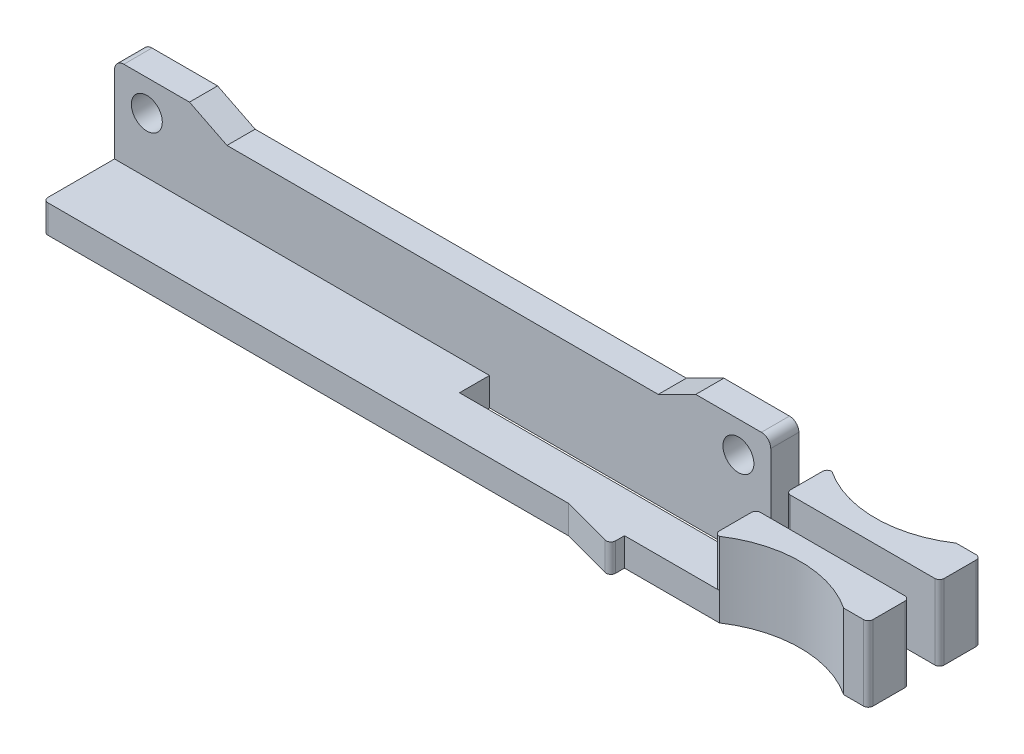
SolidWorks part; units mm, degrees
ref_plane "正面" through (0, 0, 0) normal (0, 0, 1) x (1, 0, 0)
ref_plane "平面" through (0, 0, 0) normal (0, 1, 0) x (1, 0, 0)
ref_plane "右側面" through (0, 0, 0) normal (1, 0, 0) x (0, 0, -1)
sketch "ｽｹｯﾁ2" plane through (0, 0, 0) normal (0, 1, 0) x (1, 0, 0)
  line L0 (70, 7.6) -> (40, 7.6)
  line L1 (0.5, 0) -> (56, 0)
  line L2 (0, 0.5) -> (0, 11.5)
  line L3 (0.5, 12) -> (70, 12)
  line L5 (40, 7.6) -> (40, 4.4)
  line L6 (40, 4.4) -> (70, 4.4)
  line L8 (56, 0) -> (61.3712, -1.4323)
  line L9 (62, -0.9492) -> (62, 0)
  line L10 (62, 0) -> (70, 0)
  line L11 (70, 12) -> (72.1168, 12)
  line L12 (88, 11.5) -> (88, 8.1)
  line L13 (87.5, 7.6) -> (70, 7.6)
  line L14 (70, 4.4) -> (87.5, 4.4)
  line L15 (88, 3.9) -> (88, 0.5)
  line L16 (87.5, 0) -> (85.3832, 0)
  line L17 (78.75, 12) -> (78.75, 22) construction
  line L18 (78.75, 12) -> (78.75, 10) construction
  line L19 (0, 6) -> (88, 6) construction
  line L20 (78.75, 0) -> (78.75, 2) construction
  line L21 (78.75, 0) -> (78.75, -10) construction
  line L22 (72.1168, 0) -> (70, 0)
  line L23 (85.3832, 12) -> (87.5, 12)
  arc A0 (61.3712, -1.4323) -> (62, -0.9492) centre (61.5, -0.9492) ccw
  arc A1 (72.1168, 12) -> (85.3832, 12) centre (78.75, 22) ccw
  arc A2 (72.1168, 0) -> (85.3832, 0) centre (78.75, -10) cw
  arc A3 (87.5, 12) -> (88, 11.5) centre (87.5, 11.5) cw
  arc A4 (88, 0.5) -> (87.5, 0) centre (87.5, 0.5) cw
  arc A5 (87.5, 4.4) -> (88, 3.9) centre (87.5, 3.9) cw
  arc A6 (88, 8.1) -> (87.5, 7.6) centre (87.5, 8.1) cw
  arc A7 (0.5, 0) -> (0, 0.5) centre (0.5, 0.5) cw
  arc A8 (0, 11.5) -> (0.5, 12) centre (0.5, 11.5) cw
  point P14 (62, -1.6)
  point P33 (78.75, 4.4)
  point P35 (78.75, 7.6)
  point P39 (88, 12)
  point P46 (88, 7.6)
  point P49 (0, 0)
  point P52 (0, 12)
  dimension "D8" = 0.5
  dimension "D12" = 0.5
  dimension "D13" = 0.5
  dimension "D14" = 0.5
  dimension "D1" = 70
  dimension "D2" = 18
  dimension "D3" = 3.2
  dimension "D4" = 30
  dimension "D5" = 8
  dimension "D6" = 6
  dimension "6" = 1.6
  dimension "D9" = 12
  dimension "D10" = 2
  dimension "D11" = 10
extrude "ﾎﾞｽ - 押し出し1" add sketch "ｽｹｯﾁ2" along normal blind 3
sketch "ｽｹｯﾁ4" plane through (0, 3, 0) normal (0, 1, 0) x (1, 0, 0)
  line L0 (0, 11.5) -> (0, 0.5) construction
  line L1 (70, 7.6) -> (0, 7.6)
  line L2 (70, 7.6) -> (70, 10.6)
  line L3 (70, 10.6) -> (0, 10.6)
  line L4 (0, 7.6) -> (0, 10.6)
  line L5 (40, 7.6) -> (87.5, 7.6) construction
  dimension "D1" = 3
  dimension "D2" = 70
extrude "ﾎﾞｽ - 押し出し2" add sketch "ｽｹｯﾁ4" along normal blind 9.25
sketch "ｽｹｯﾁ5" plane through (0, 0, -7.6) normal (0, 0, 1) x (1, 0, 0)
  line L0 (35, 12.25) -> (35, 8.95) construction
  line L1 (0, 12.25) -> (70, 12.25) construction
  line L2 (35, 8.95) -> (35, 3) construction
  line L4 (0.5, 3) -> (56, 3) construction
  line L7 (3.45, 8.95) -> (66.55, 8.95) construction
  circle A30 centre (3.45, 8.95) radius 1.65
  circle A31 centre (66.55, 8.95) radius 1.65
  point P9 (35, 8.95)
  point P17 (67.7, 8.7)
  point P20 (3.45, 8.7)
  dimension "D3" = 63.1
  dimension "D2" = 3.3
  dimension "D1" = 5.95
extrude "ｶｯﾄ - 押し出し1" cut sketch "ｽｹｯﾁ5" against normal up to next
fillet "ﾌｨﾚｯﾄ1" radius 1 2 edges at (70, 12.25, -9.1) (0, 12.25, -9.1)
sketch "ｽｹｯﾁ6" plane through (0, 3, 0) normal (0, 1, 0) x (1, 0, 0)
  line L0 (72.1168, 12) -> (72.1168, 7.6) construction
  line L1 (72.1168, 0) -> (72.1168, 4.4) construction
  line L23 (88, 11.5) -> (88, 8.1)
  line L24 (85.3832, 12) -> (87.5, 12)
  line L25 (88, 11.5) -> (88, 8.1)
  line L26 (85.3832, 12) -> (87.5, 12)
  line L32 (70, 7.6) -> (87.5, 7.6) construction
  line L33 (88, 3.9) -> (88, 0.5)
  line L34 (87.5, 0) -> (85.3832, 0)
  line L35 (88, 3.9) -> (88, 0.5)
  line L36 (87.5, 0) -> (85.3832, 0)
  line L39 (87.5, 4.4) -> (40, 4.4) construction
  line L41 (71.6168, 11.5) -> (71.6168, 8.1)
  line L42 (71.6168, 0.5) -> (71.6168, 3.9)
  line L43 (72.1168, 7.6) -> (87.5, 7.6)
  line L44 (72.1168, 4.4) -> (87.5, 4.4)
  arc A0 (71.6168, 3.9) -> (72.1168, 4.4) centre (72.1168, 3.9) cw
  arc A1 (71.6168, 8.1) -> (72.1168, 7.6) centre (72.1168, 8.1) ccw
  arc A36 (87.5, 7.6) -> (88, 8.1) centre (87.5, 8.1) ccw
  arc A37 (88, 11.5) -> (87.5, 12) centre (87.5, 11.5) ccw
  arc A38 (72.1168, 12) -> (85.3832, 12) centre (78.75, 22) ccw
  arc A39 (87.5, 7.6) -> (88, 8.1) centre (87.5, 8.1) ccw
  arc A40 (88, 11.5) -> (87.5, 12) centre (87.5, 11.5) ccw
  arc A41 (72.1168, 12) -> (85.3832, 12) centre (78.75, 22) ccw
  arc A48 (71.6168, 0.5) -> (72.1168, 0) centre (72.1168, 0.5) ccw
  arc A49 (72.1168, 12) -> (71.6168, 11.5) centre (72.1168, 11.5) ccw
  arc A51 (88, 3.9) -> (87.5, 4.4) centre (87.5, 3.9) ccw
  arc A52 (87.5, 0) -> (88, 0.5) centre (87.5, 0.5) ccw
  arc A53 (85.3832, 0) -> (72.1168, 0) centre (78.75, -10) ccw
  arc A54 (88, 3.9) -> (87.5, 4.4) centre (87.5, 3.9) ccw
  arc A55 (87.5, 0) -> (88, 0.5) centre (87.5, 0.5) ccw
  arc A56 (85.3832, 0) -> (72.1168, 0) centre (78.75, -10) ccw
  point P14 (71.6168, 4.4)
  point P17 (71.6168, 7.6)
  dimension "D3" = 1
  dimension "D4" = 0.5
  dimension "D1" = 0
  dimension "D2" = 0
extrude "ﾎﾞｽ - 押し出し3" add sketch "ｽｹｯﾁ6" along normal blind 5
sketch "ｽｹｯﾁ7" plane through (0, 0, -7.6) normal (0, 0, 1) x (1, 0, 0)
  line L0 (8, 12.25) -> (12, 10.25)
  line L1 (1, 12.25) -> (69, 12.25) construction
  line L2 (12, 10.25) -> (58, 10.25)
  line L3 (58, 10.25) -> (62, 12.25)
  line L4 (62, 12.25) -> (8, 12.25)
  line L5 (8, 12.25) -> (0, 12.25) construction
  line L6 (62, 12.25) -> (70, 12.25) construction
  line L7 (0, 11.25) -> (0, 3) construction
  line L8 (70, 11.25) -> (70, 3) construction
  line L9 (8, 12.25) -> (8, 10.25) construction
  line L10 (8, 10.25) -> (12, 10.25) construction
  line L11 (58, 10.25) -> (62, 10.25) construction
  line L12 (62, 10.25) -> (62, 12.25) construction
  dimension "D1" = 8
  dimension "D2" = 2
  dimension "D3" = 4
extrude "ｶｯﾄ - 押し出し2" cut sketch "ｽｹｯﾁ7" against normal up to next
